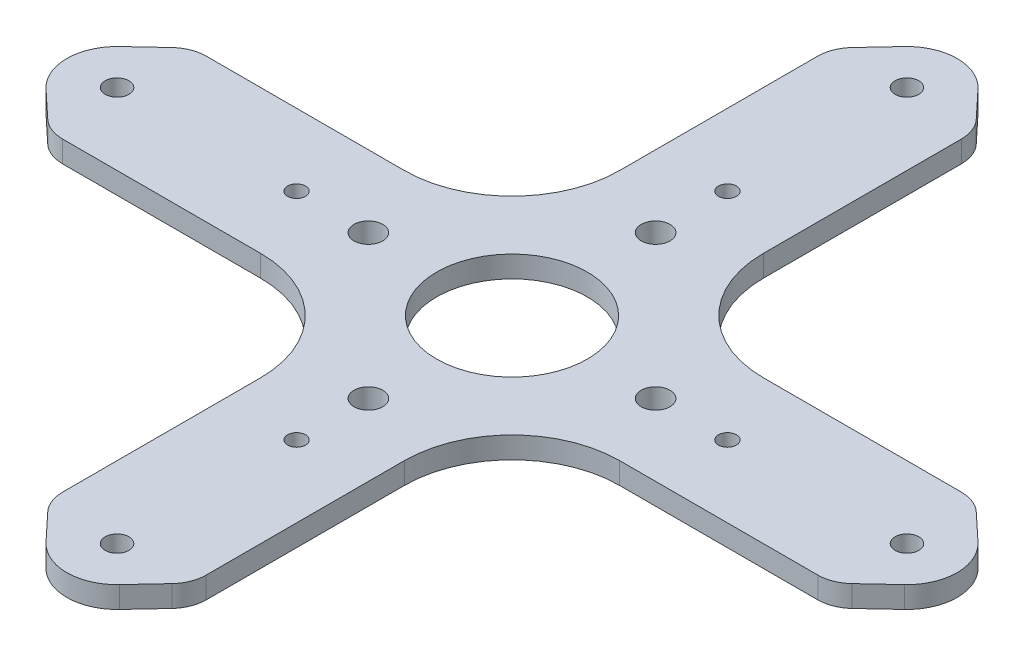
SolidWorks part; units mm, degrees
material "Alloy Steel (SS)"
ref_plane "Front Plane" through (0, 0, 0) normal (0, 0, 1) x (1, 0, 0)
ref_plane "Top Plane" through (0, 0, 0) normal (0, 1, 0) x (1, 0, 0)
ref_plane "Right Plane" through (0, 0, 0) normal (1, 0, 0) x (0, 0, -1)
sketch "Sketch1" plane through (0, 0, 0) normal (0, 1, 0) x (1, 0, 0)
  line L17 (10, 10) -> (54.5563, 10)
  line L18 (54.5563, 10) -> (59.7818, 5.1122)
  line L19 (10, -10) -> (54.5563, -10)
  line L20 (54.5563, -10) -> (59.7818, -5.1122)
  line L21 (55, 0) -> (0, 0) construction
  line L22 (54.5563, 10) -> (54.5563, -10) construction
  line L23 (10, -10) -> (10, -54.5563)
  line L24 (10, -54.5563) -> (5.1122, -59.7818)
  line L25 (-10, -54.5563) -> (-5.1122, -59.7818)
  line L26 (-10, -10) -> (-10, -54.5563)
  line L27 (-10, -10) -> (-54.5563, -10)
  line L28 (-54.5563, -10) -> (-59.7818, -5.1122)
  line L29 (-54.5563, 10) -> (-59.7818, 5.1122)
  line L30 (-10, 10) -> (-54.5563, 10)
  line L31 (-10, 10) -> (-10, 54.5563)
  line L32 (-10, 54.5563) -> (-5.1122, 59.7818)
  line L33 (10, 54.5563) -> (5.1122, 59.7818)
  line L34 (10, 10) -> (10, 54.5563)
  circle A0 centre (-20, 0) radius 2
  circle A1 centre (0, 20) radius 2
  circle A2 centre (20, 0) radius 2
  circle A3 centre (0, -20) radius 2
  circle A4 centre (0, 0) radius 10.5
  arc A5 (59.7818, 5.1122) -> (59.7818, -5.1122) centre (55, 0) cw
  circle A6 centre (0, 0) radius 60 construction
  arc A7 (5.1122, -59.7818) -> (-5.1122, -59.7818) centre (0, -55) cw
  arc A8 (-59.7818, -5.1122) -> (-59.7818, 5.1122) centre (-55, 0) cw
  arc A9 (-5.1122, 59.7818) -> (5.1122, 59.7818) centre (0, 55) cw
  point P30 (0, 0)
  point P49 (0, 0)
  dimension "D2" = 4
  dimension "D6" = 21
  dimension "D4" = 7
  dimension "D5" = 120
  dimension "D1" = 20
  dimension "D3" = 4
  dimension "D7" = 20
  dimension "D9" = 55
  dimension "D8" = 4
extrude "Boss-Extrude1" add sketch "Sketch1" along normal blind 3
fillet "Fillet1" radius 15 4 edges at (-10, 1.5, 10) (-10, 1.5, -10) (10, 1.5, -10) (10, 1.5, 10)
fillet "Fillet2" radius 5 8 edges at (-54.5563, 1.5, 10) (-54.5563, 1.5, -10) (-10, 1.5, -54.5563) (10, 1.5, -54.5563) (54.5563, 1.5, -10) (54.5563, 1.5, 10) (-10, 1.5, 54.5563) (10, 1.5, 54.5563)
hole_wizard "M4x0.7 Tapped Hole1" positions "Sketch2" profile "Sketch3" tap size "M4x0.7" standard "ANSI Metric" end condition through all
sketch "Sketch2" plane through (0, 0, 0) normal (0, -1, 0) x (-1, 0, 0)
  point P0 (0, -55)
  point P3 (-55, 0)
  point P6 (0, 55)
  point P9 (55, 0)
sketch "Sketch3" plane through (0, 0, 55) normal (1, 0, 0) x (0, 0, -1)
  line L0 (0, 0) -> (0, 3)
  line L1 (0, 3) -> (1.65, 3)
  line L2 (1.65, 3) -> (1.65, 0)
  line L5 (1.65, 0) -> (0, 0)
  line L11 (0, -6.35) -> (0, 107.95) construction
  dimension "Thru Tap Drill Dia." = 3.3
  dimension "Thru Tap Drill Depth" = 3
cosmetic thread "Hole Thread1" parameters "D2"=4
cosmetic thread "Hole Thread2" parameters "D2"=4
cosmetic thread "Hole Thread3" parameters "D2"=4
cosmetic thread "Hole Thread4" parameters "D2"=4
hole_wizard "M3x0.5 Tapped Hole1" positions "Sketch4" profile "Sketch5" tap size "M3x0.5" standard "ANSI Metric" end condition through all
sketch "Sketch4" plane through (0, 0, 0) normal (0, -1, 0) x (-1, 0, 0)
  line L0 (0, -55) -> (0, 0) construction
  point P0 (0, -30)
  point P15 (-30, 0)
  point P16 (0, 30)
  point P17 (30, 0)
  point P18 (0, 0)
  dimension "D1" = 30
  dimension "D2" = 4
sketch "Sketch5" plane through (0, 0, 30) normal (1, 0, 0) x (0, 0, -1)
  line L0 (0, 0) -> (0, 3)
  line L1 (0, 3) -> (1.25, 3)
  line L2 (1.25, 3) -> (1.25, 0)
  line L5 (1.25, 0) -> (0, 0)
  line L11 (0, -6.35) -> (0, 107.95) construction
  dimension "Thru Tap Drill Dia." = 2.5
  dimension "Thru Tap Drill Depth" = 3
cosmetic thread "Hole Thread5" parameters "D2"=3
cosmetic thread "Hole Thread6" parameters "D2"=3
cosmetic thread "Hole Thread7" parameters "D2"=3
cosmetic thread "Hole Thread8" parameters "D2"=3
